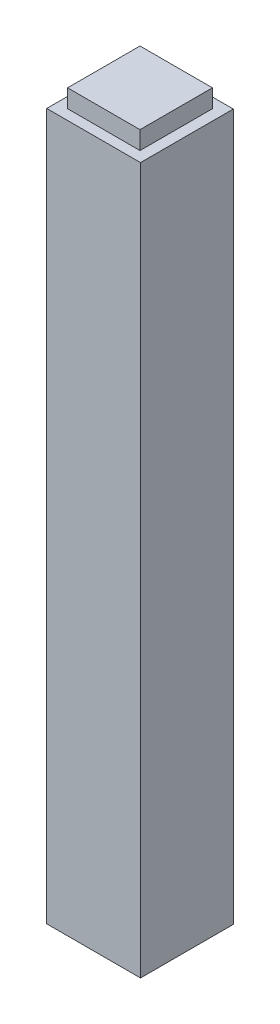
SolidWorks part; units mm, degrees
other "COLL.BOX-Estrusione-Estrusione2"
ref_plane "Piano frontale" through (0, 0, 0) normal (0, 0, 1) x (1, 0, 0)
ref_plane "Piano superiore" through (0, 0, 0) normal (0, 1, 0) x (1, 0, 0)
ref_plane "Piano destro" through (0, 0, 0) normal (1, 0, 0) x (0, 0, -1)
sketch "Schizzo2" plane through (0, 0, 0) normal (0, 1, 0) x (1, 0, 0)
  line L1 (-20, -20) -> (20, -20)
  line L2 (-20, -20) -> (-20, 20)
  line L3 (-20, 20) -> (20, 20)
  line L4 (20, -20) -> (20, 20)
  line L5 (-20, -20) -> (20, 20) construction
  line L6 (-20, 20) -> (20, -20) construction
  point P0 (0, 0)
  dimension "D1" = 40
  dimension "D2" = 40
extrude "Estrusione-Estrusione1" add sketch "Schizzo2" along normal blind 400
sketch "Schizzo3" plane through (0, 0, 0) normal (0, -1, 0) x (-1, 0, 0)
  line L1 (-25.8991, -25.6196) -> (25.8991, -25.6196)
  line L2 (-25.8991, -25.6196) -> (-25.8991, 25.6196)
  line L3 (-25.8991, 25.6196) -> (25.8991, 25.6196)
  line L4 (25.8991, -25.6196) -> (25.8991, 25.6196)
  line L5 (-25.8991, -25.6196) -> (25.8991, 25.6196) construction
  line L6 (-25.8991, 25.6196) -> (25.8991, -25.6196) construction
  point P0 (0, 0)
extrude "Estrusione-Estrusione2" add sketch "Schizzo3" against normal blind 390 separate body
